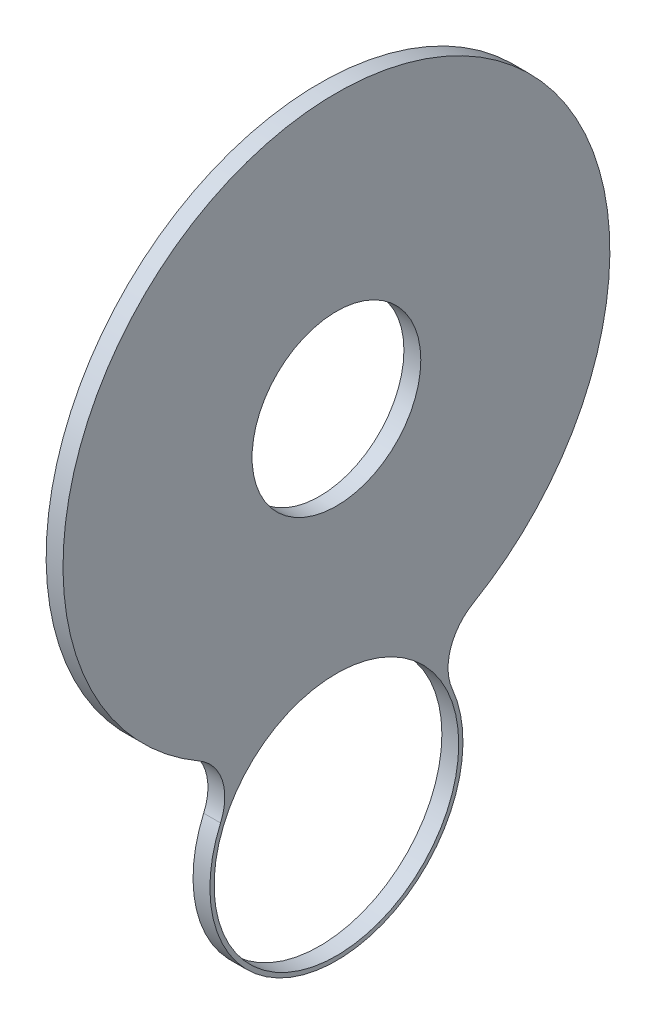
SolidWorks part; units mm, degrees
ref_plane "Front Plane" through (0, 0, 0) normal (0, 0, 1) x (1, 0, 0)
ref_plane "Top Plane" through (0, 0, 0) normal (0, 1, 0) x (1, 0, 0)
ref_plane "Right Plane" through (0, 0, 0) normal (1, 0, 0) x (0, 0, -1)
sketch "Sketch1" plane through (0, 0, 0) normal (1, 0, 0) x (0, 0, -1)
  arc A0 (81.1531, 9.412) -> (-81.1531, 9.412) centre (0, 149.7013) ccw
  arc A1 (-68.6963, -28.5949) -> (68.6963, -28.5949) centre (0, -58.6917) ccw
  circle A2 centre (0, 149.7013) radius 50
  arc A3 (68.6963, -28.5949) -> (81.1531, 9.412) centre (96.1749, -16.5562) cw
  arc A4 (-68.6963, -28.5949) -> (-81.1531, 9.412) centre (-96.1749, -16.5562) ccw
  dimension "D1" = 324.1414
  dimension "D2" = 150
  dimension "D4" = 100
  dimension "D5" = 30
  dimension "D3" = 208.393
extrude "Boss-Extrude1" add sketch "Sketch1" along normal blind 10
sketch "Sketch2" plane through (10, 0, 0) normal (1, 0, 0) x (0, 0, -1)
  circle A0 centre (0, -58.6917) radius 72.5
  dimension "D1" = 145
extrude "Cut-Extrude1" cut sketch "Sketch2" against normal through all
